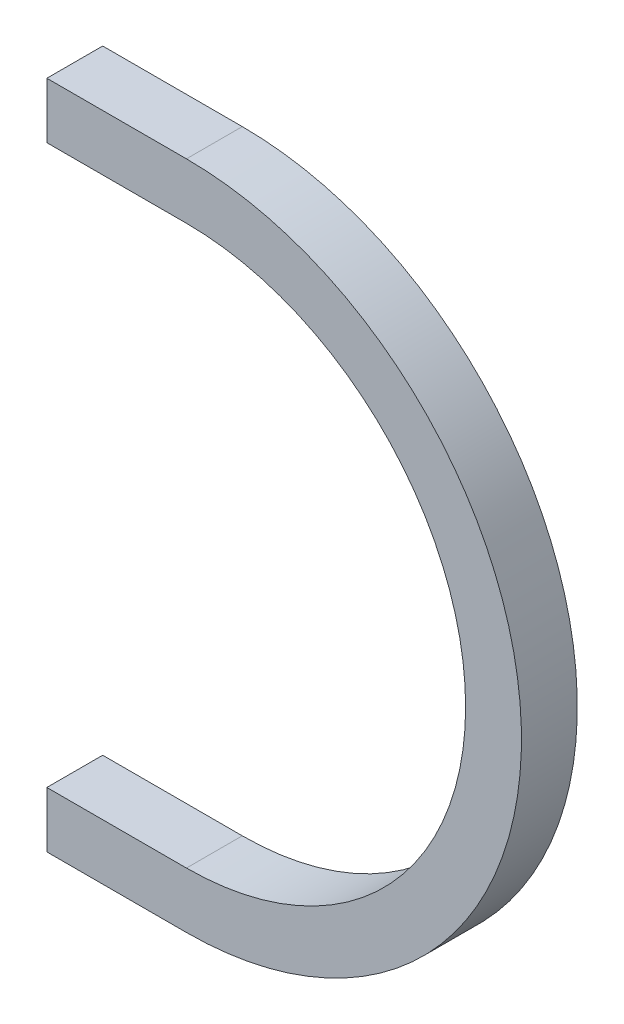
SolidWorks part; units mm, degrees
ref_plane "Front Plane" through (0, 0, 0) normal (0, 0, 1) x (1, 0, 0)
ref_plane "Top Plane" through (0, 0, 0) normal (0, 1, 0) x (1, 0, 0)
ref_plane "Right Plane" through (0, 0, 0) normal (1, 0, 0) x (0, 0, -1)
sketch "Sketch2" plane through (0, 0, 0) normal (0, 0, 1) x (1, 0, 0)
  line L0 (0, 0) -> (0, -200)
  line L1 (0, -200) -> (500, -200)
  line L2 (500, -2200) -> (0, -2200)
  line L3 (0, -2200) -> (0, -2400)
  line L4 (0, 0) -> (500, 0)
  line L5 (0, -2400) -> (500, -2400)
  arc A0 (500, -2200) -> (500, -200) centre (500, -1200) ccw
  arc A1 (500, 0) -> (500, -2400) centre (500, -1200) cw
  dimension "D4" = 2000
  dimension "D1" = 200
  dimension "D2" = 500
  dimension "D3" = 2000
  dimension "D5" = 200
extrude "Boss-Extrude1" add sketch "Sketch2" along normal blind 200
